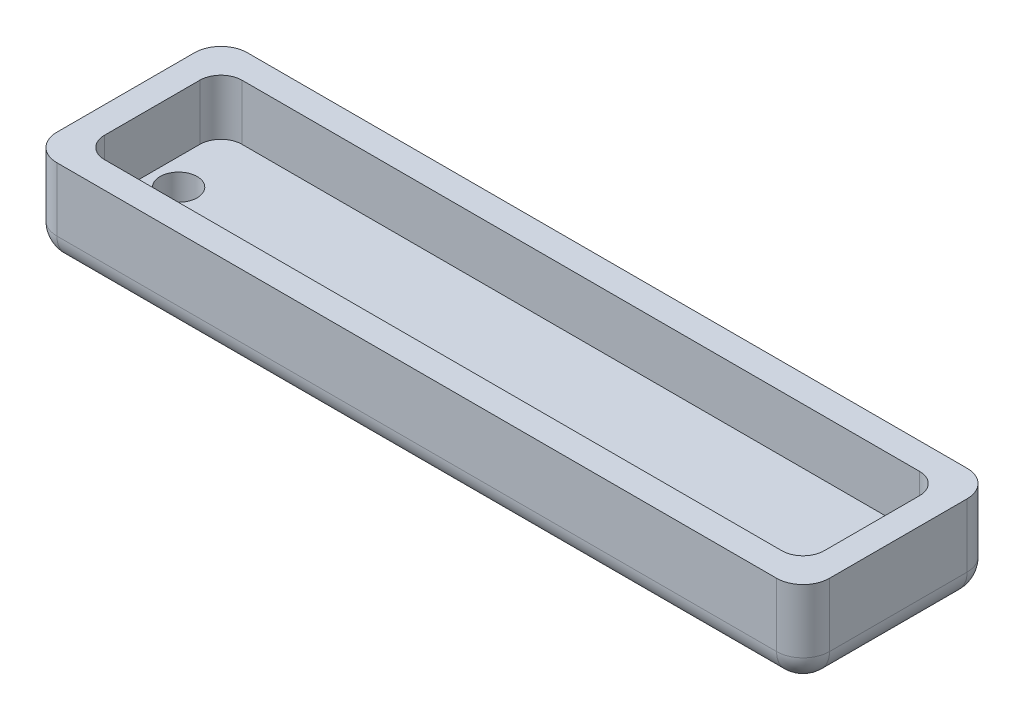
SolidWorks part; units mm, degrees
ref_plane "Front Plane" through (0, 0, 0) normal (0, 0, 1) x (1, 0, 0)
ref_plane "Top Plane" through (0, 0, 0) normal (0, 1, 0) x (1, 0, 0)
ref_plane "Right Plane" through (0, 0, 0) normal (1, 0, 0) x (0, 0, -1)
sketch "Sketch1" plane through (0, 0, 0) normal (0, 1, 0) x (1, 0, 0)
  line L1 (-18.542, -4.572) -> (18.542, -4.572)
  line L2 (-18.542, -4.572) -> (-18.542, 4.572)
  line L3 (-18.542, 4.572) -> (18.542, 4.572)
  line L4 (18.542, -4.572) -> (18.542, 4.572)
  line L5 (-18.542, -4.572) -> (18.542, 4.572) construction
  line L6 (-18.542, 4.572) -> (18.542, -4.572) construction
  point P0 (0, 0)
  dimension "D1" = 37.084
  dimension "D2" = 9.144
extrude "Boss-Extrude1" add sketch "Sketch1" along normal blind 4.318
sketch "Sketch2" plane through (0, 4.318, 0) normal (0, 1, 0) x (1, 0, 0)
  line L0 (-18.542, 4.572) -> (-18.542, -4.572) construction
  line L1 (-17.272, 3.302) -> (17.272, 3.302)
  line L2 (-17.272, 3.302) -> (-17.272, -3.302)
  line L3 (-17.272, -3.302) -> (17.272, -3.302)
  line L4 (17.272, 3.302) -> (17.272, -3.302)
  line L5 (-17.272, 3.302) -> (17.272, -3.302) construction
  line L6 (-17.272, -3.302) -> (17.272, 3.302) construction
  line L7 (-18.542, -4.572) -> (18.542, -4.572) construction
  point P0 (0, 0)
  dimension "D1" = 1.27
  dimension "D2" = 1.27
extrude "Cut-Extrude3" cut sketch "Sketch2" against normal offset from surface (2.667 mm away) 1.651 up to face at (0, 0, 0)
fillet "Fillet1" radius 1.27 8 edges at (18.542, 0, 0) (18.542, 2.159, -4.572) (0, 0, -4.572) (0, 0, 4.572) (-18.542, 0, 0) (-18.542, 2.159, -4.572) (-18.542, 2.159, 4.572) (18.542, 2.159, 4.572)
fillet "Fillet2" radius 1.016 4 edges at (17.272, 2.9845, 3.302) (17.272, 2.9845, -3.302) (-17.272, 2.9845, 3.302) (-17.272, 2.9845, -3.302)
sketch "Sketch11" plane through (0, 1.651, 0) normal (0, 1, 0) x (1, 0, 0)
  line L0 (-17.272, 0) -> (17.272, 0) construction
  line L2 (-17.272, 2.286) -> (-17.272, -2.286) construction
  line L4 (0, 0) -> (0, -10.523) construction
  line L5 (17.272, -2.286) -> (17.272, 2.286) construction
  circle A0 centre (-16.002, 0) radius 0.889
  circle A1 centre (16.002, 0) radius 0.889
  dimension "D1" = 1.27
  dimension "D2" = 1.778
extrude "Cut-Extrude4" cut sketch "Sketch11" against normal through all
